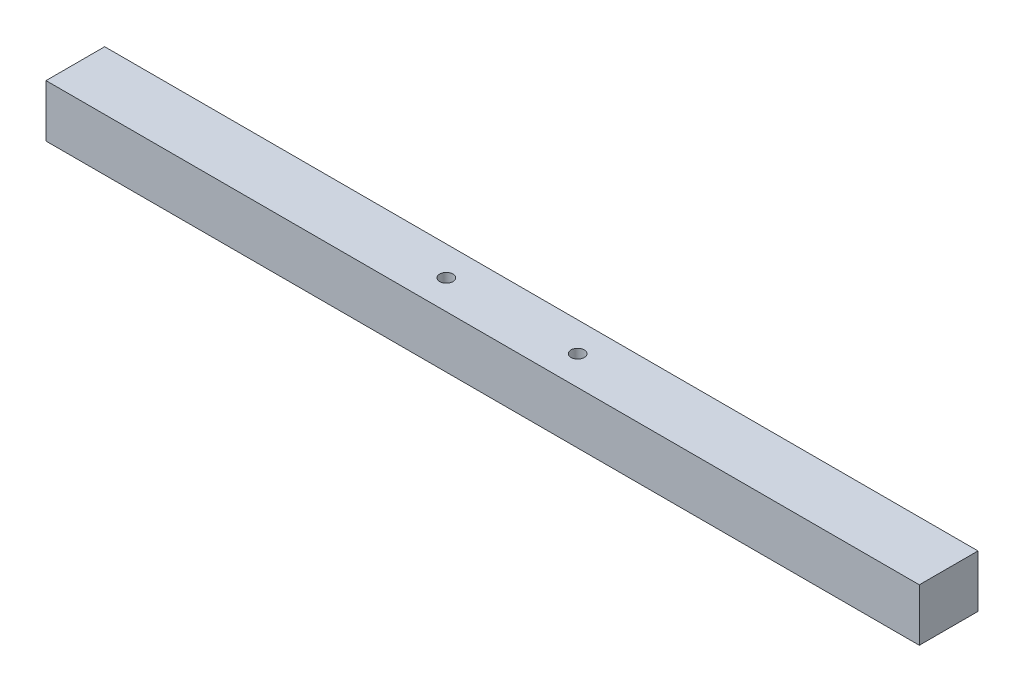
SolidWorks part; units mm, degrees
ref_plane "Alzado" through (0, 0, 0) normal (0, 0, 1) x (1, 0, 0)
ref_plane "Planta" through (0, 0, 0) normal (0, 1, 0) x (1, 0, 0)
ref_plane "Vista lateral" through (0, 0, 0) normal (1, 0, 0) x (0, 0, -1)
sketch "Croquis1" plane through (0, 0, 0) normal (0, 1, 0) x (1, 0, 0)
  line L0 (0, 0) -> (-18.8, 0) construction
  line L1 (125, -8.4) -> (-125, -8.4)
  line L2 (125, -8.4) -> (125, 8.4)
  line L3 (125, 8.4) -> (-125, 8.4)
  line L4 (-125, -8.4) -> (-125, 8.4)
  line L5 (125, -8.4) -> (-125, 8.4) construction
  line L6 (125, 8.4) -> (-125, -8.4) construction
  line L7 (0, 0) -> (18.8, 0) construction
  circle A0 centre (-18.8, 0) radius 1.9
  circle A1 centre (18.8, 0) radius 1.9
  point P0 (0, 0)
  dimension "D3" = 3.8
  dimension "D1" = 16.8
  dimension "D2" = 250
  dimension "D4" = 18.8
extrude "Saliente-Extruir1" add sketch "Croquis1" along normal blind 15
